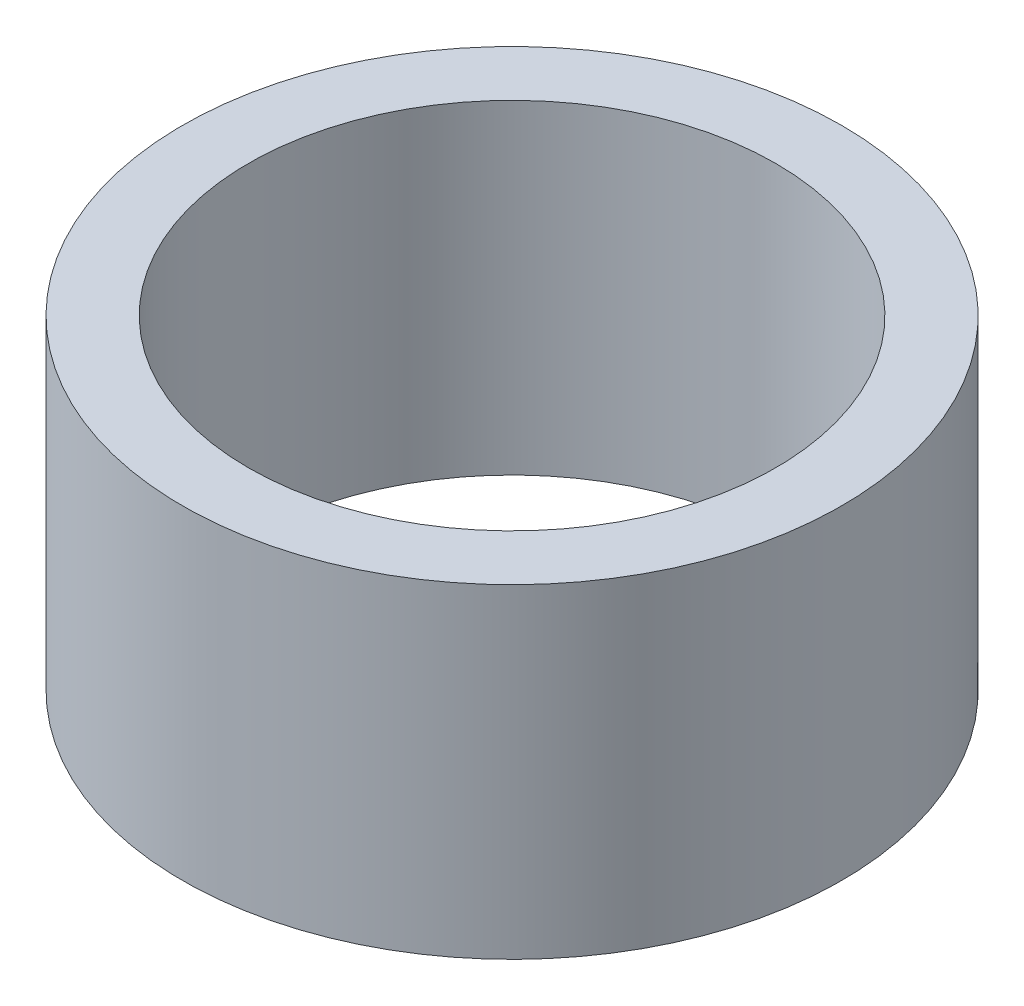
SolidWorks part; units mm, degrees
ref_plane "Front Plane" through (0, 0, 0) normal (0, 0, 1) x (1, 0, 0)
ref_plane "Top Plane" through (0, 0, 0) normal (0, 1, 0) x (1, 0, 0)
ref_plane "Right Plane" through (0, 0, 0) normal (1, 0, 0) x (0, 0, -1)
sketch "Sketch1" plane through (0, 0, 0) normal (0, 0, 1) x (1, 0, 0)
  line L0 (0, 0) -> (0, 40889.2322) construction
  line L1 (16.51, 0) -> (16.51, 20.32)
  line L2 (16.51, 20.32) -> (20.6375, 20.32)
  line L3 (20.6375, 20.32) -> (20.6375, 0)
  line L4 (20.6375, 0) -> (16.51, 0)
  point P5 (16.51, 10.16)
  point P8 (20.6375, 10.16)
  point P9 (16.244, 5.7352)
  point P10 (17.7059, 0)
  point P11 (20.6375, 10.524)
  dimension "D1" = 16.51
  dimension "D2" = 20.6375
  dimension "D3" = 20.32
revolve "Revolve1" add sketch "Sketch1" angle 360 about L0
